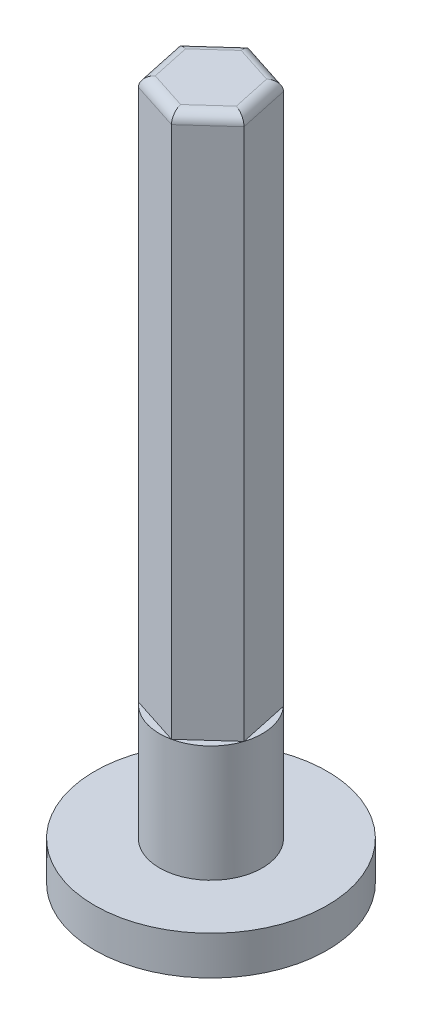
SolidWorks part; units mm, degrees
ref_plane "Alzado" through (0, 0, 0) normal (0, 0, 1) x (1, 0, 0)
ref_plane "Planta" through (0, 0, 0) normal (0, 1, 0) x (1, 0, 0)
ref_plane "Vista lateral" through (0, 0, 0) normal (1, 0, 0) x (0, 0, -1)
sketch "Croquis1" plane through (0, 0, 0) normal (0, 1, 0) x (1, 0, 0)
  circle A0 centre (0, 0) radius 9
  dimension "D1" = 18
extrude "Saliente-Extruir1" add sketch "Croquis1" along normal blind 3
sketch "Croquis2" plane through (0, 3, 0) normal (0, 1, 0) x (1, 0, 0)
  circle A0 centre (0, 0) radius 3.975
  dimension "D1" = 7.95
extrude "Saliente-Extruir2" add sketch "Croquis2" along normal blind 9
sketch "Croquis3" plane through (0, 12, 0) normal (0, 1, 0) x (1, 0, 0)
  line L1 (3.7824, -1.2223) -> (2.9497, 2.6645)
  line L2 (2.9497, 2.6645) -> (-0.8327, 3.8868)
  line L3 (-0.8327, 3.8868) -> (-3.7824, 1.2223)
  line L4 (-3.7824, 1.2223) -> (-2.9497, -2.6645)
  line L5 (-2.9497, -2.6645) -> (0.8327, -3.8868)
  line L6 (0.8327, -3.8868) -> (3.7824, -1.2223)
  circle A0 centre (0, 0) radius 3.4425 construction
  circle A2 centre (0, 0) radius 3.975
  circle A3 centre (0, 0) radius 3.975
  dimension "D1" = 0
  dimension "D2" = 6.8849
extrude "Saliente-Extruir3" add sketch "Croquis3" along normal blind 42 contours L5 L6 L1 L2 L3 L4
fillet "Redondeo1" radius 0.8 6 edges at (2.3076, 54, 2.5545) (3.3661, 54, -0.7211) (1.0585, 54, -3.2757) (-2.3076, 54, -2.5545) (-3.3661, 54, 0.7211) (-1.0585, 54, 3.2757)
